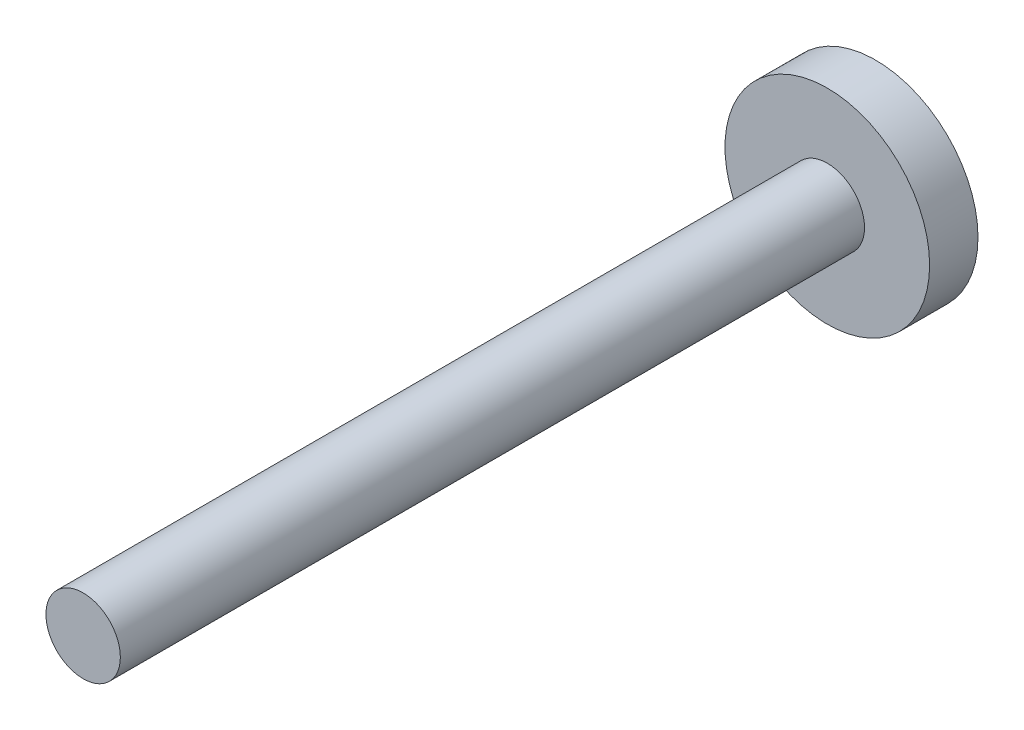
SolidWorks part; units mm, degrees
ref_plane "Plan de face" through (0, 0, 0) normal (0, 0, 1) x (1, 0, 0)
ref_plane "Plan de dessus" through (0, 0, 0) normal (0, 1, 0) x (1, 0, 0)
ref_plane "Plan de droite" through (0, 0, 0) normal (1, 0, 0) x (0, 0, -1)
sketch "Esquisse1" plane through (0, 0, 0) normal (0, 0, 1) x (1, 0, 0)
  circle A0 centre (0, 0) radius 1
  dimension "D1" = 2
extrude "Boss.-Extru.1" add sketch "Esquisse1" along normal blind 20
cosmetic thread "Représentation de filetage1" parameters "D1"=18, "D2"=1.548
sketch "Esquisse2" plane through (0, 0, 0) normal (0, 0, 1) x (1, 0, 0)
  circle A0 centre (0, 0) radius 2.75
  dimension "D1" = 5.5
extrude "Boss.-Extru.2" add sketch "Esquisse2" against normal blind 1.3
